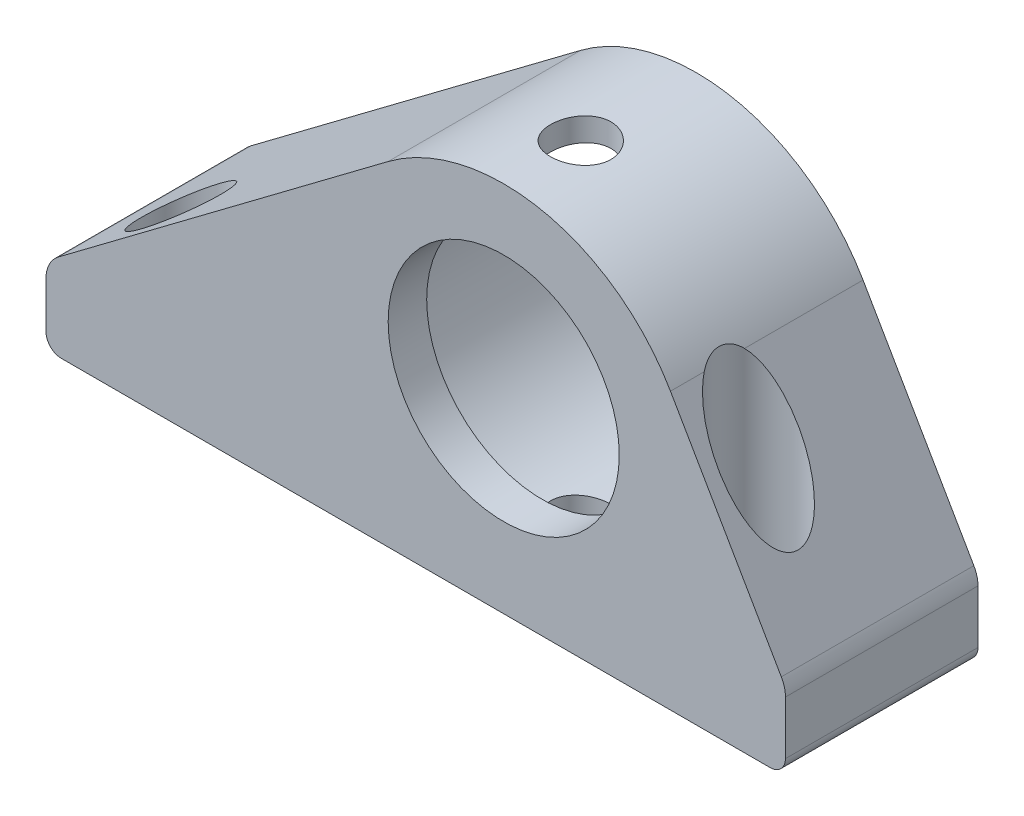
SolidWorks part; units mm, degrees
ref_plane "Alzado" through (0, 0, 0) normal (0, 0, 1) x (1, 0, 0)
ref_plane "Planta" through (0, 0, 0) normal (0, 1, 0) x (1, 0, 0)
ref_plane "Vista lateral" through (0, 0, 0) normal (1, 0, 0) x (0, 0, -1)
sketch "Croquis1" plane through (0, 0, 0) normal (0, 0, 1) x (1, 0, 0)
  line L4 (30.48, 0) -> (-30.48, 0)
  line L5 (-30.48, 0) -> (-30.48, 6.35)
  line L6 (-30.48, 6.35) -> (12.0465, 38.2778)
  line L7 (12.0465, 38.2778) -> (30.48, 6.35)
  line L8 (30.48, 6.35) -> (30.48, 0)
  line L9 (0, 0) -> (0, 44.0233) construction
  point P11 (0, 0)
  dimension "D1" = 6.35
  dimension "D2" = 38.2778
  dimension "D3" = 60.96
  dimension "D4" = 30
extrude "Saliente-Extruir1" add sketch "Croquis1" along normal blind 15.875
fillet "Redondeo1" radius 15.875 1 edges at (12.0465, 38.2778, 7.9375)
sketch "Croquis2" plane through (0, 0, 15.875) normal (0, 0, 1) x (1, 0, 0)
  line L0 (30.48, 6.35) -> (21.0022, 22.7661) construction
  circle A0 centre (7.254, 16.0986) radius 9.525
  arc A1 (21.0022, 22.7661) -> (-2.2773, 27.5239) centre (7.254, 14.8286) ccw construction
  dimension "D1" = 5.08
  dimension "D2" = 19.05
  dimension "D3" = 15.24
extrude "Cortar-Extruir1" cut sketch "Croquis2" against normal up to next
sketch "Croquis3" plane through (0, 0, 15.875) normal (0, 0, 1) x (1, 0, 0)
  circle A0 centre (7.254, 16.0986) radius 12.7
  dimension "D1" = 25.4
extrude "Cortar-Extruir2" cut sketch "Croquis3" against normal through all from offset 3.175 offset against normal yes
sketch "Croquis4" plane through (0, 0, 0) normal (0, -1, 0) x (1, 0, 0)
  line L0 (-30.48, 15.875) -> (-30.48, 0) construction
  line L1 (-30.48, 15.875) -> (30.48, 15.875) construction
  line L2 (0, 0) -> (0, 12.065) construction
  line L3 (-30.48, 0) -> (30.48, 0) construction
  line L4 (16.779, 15.875) -> (-2.271, 15.875) construction
  line L5 (16.779, 15.875) -> (-2.271, 15.875)
  circle A0 centre (-23.8125, 11.43) radius 3.2639
  circle A1 centre (23.8125, 11.43) radius 3.2639
  circle A3 centre (7.254, 9.525) radius 2.4892
  point P21 (7.254, 15.875)
  dimension "D1" = 6.5278
  dimension "D4" = 4.9784
  dimension "D5" = 6.35
  dimension "D2" = 6.6675
  dimension "D3" = 4.445
extrude "Cortar-Extruir3" cut sketch "Croquis4" against normal through all contours A3 | A0 | A1
fillet "Redondeo2" radius 1.27 2 edges at (30.48, 0, 7.9375) (-30.48, 0, 7.9375)
fillet "Redondeo3" radius 2.54 2 edges at (30.48, 6.35, 7.9375) (-30.48, 6.35, 7.9375)
